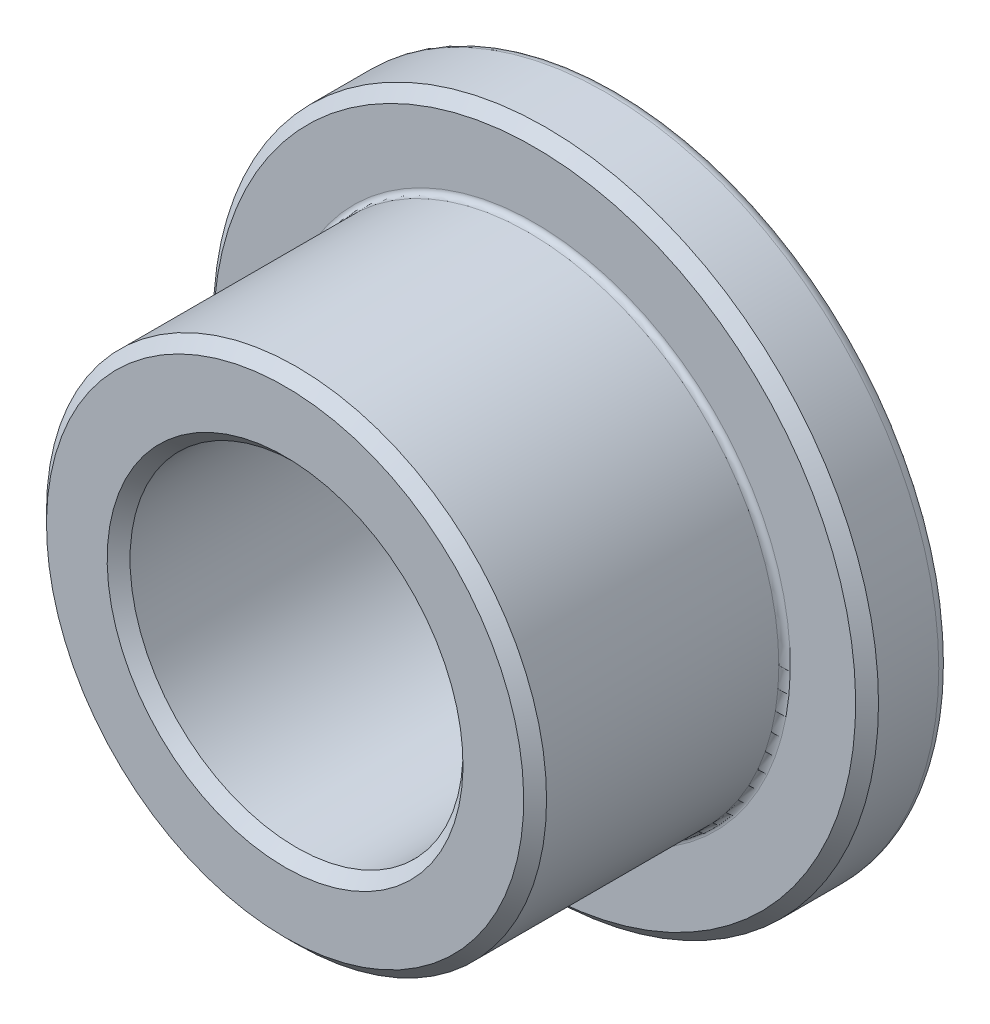
SolidWorks part; units mm, degrees
ref_plane "Front Plane" through (0, 0, 0) normal (0, 0, 1) x (1, 0, 0)
ref_plane "Top Plane" through (0, 0, 0) normal (0, 1, 0) x (1, 0, 0)
ref_plane "Right Plane" through (0, 0, 0) normal (1, 0, 0) x (0, 0, -1)
sketch "Sketch1" plane through (0, 0, 0) normal (0, 0, 1) x (1, 0, 0)
  circle A0 centre (0, 0) radius 4.005
  circle A1 centre (0, 0) radius 6.015
  circle A2 centre (0, 0) radius 8
  point P5 (0, 6.015)
  point P6 (0, 4.005)
  point P7 (0, 8)
  dimension "ID" = 8.01
  dimension "OD" = 12.03
  dimension "Flange OD" = 16
sketch "Sketch2" plane through (0, 0, 0) normal (1, 0, 0) x (0, 0, -1)
  line L0 (4, 0) -> (-4, 0)
  line L1 (4, 0) -> (4, 8)
  line L2 (4, 8) -> (2, 8)
  line L3 (2, 8) -> (2, 6.015)
  line L4 (2, 6.015) -> (-4, 6.015)
  line L5 (-4, 6.015) -> (-4, 4.005)
  line L6 (-4, 4.005) -> (4, 4.005)
  point P4 (0, 0)
  dimension "Flange Thickness" = 2
  dimension "Length" = 8
sketch "Sketch3" plane through (0, 0, 0) normal (1, 0, 0) x (0, 0, -1)
  line L0 (4, 8) -> (2, 8) construction
  line L1 (2, 8) -> (2, 6.015) construction
  line L2 (2, 6.015) -> (-4, 6.015) construction
  line L3 (-4, 4.005) -> (4, 4.005) construction
  line L4 (-4, 6.015) -> (-4, 4.005) construction
  line L5 (4, 8) -> (2, 8)
  line L6 (2, 8) -> (2, 6.015)
  line L7 (2, 6.015) -> (-4, 6.015)
  line L8 (-4, 4.005) -> (4, 4.005)
  line L9 (-4, 6.015) -> (-4, 4.005)
  line L10 (4, 8) -> (4, 4.005)
revolve "Revolve1" add sketch "Sketch3" angle 360 about L0
chamfer "Chamfer1" distance 0.275 angle 45 3 edges at (0, 8, -2) (0, 6.015, 4) (0, 4.005, 4)
fillet "Fillet1" radius 0.275 1 edges at (0, 8, -4)
fillet "Fillet2" radius 0.1375 1 edges at (0, 6.015, -2)
equation "\"D1@Chamfer1\"=\"Flange Thickness@Sketch2\"*.1375"
equation "\"D1@Fillet1\"=\"D1@Chamfer1\""
equation "\"D1@Fillet2\"=\"D1@Fillet1\"*.5"
